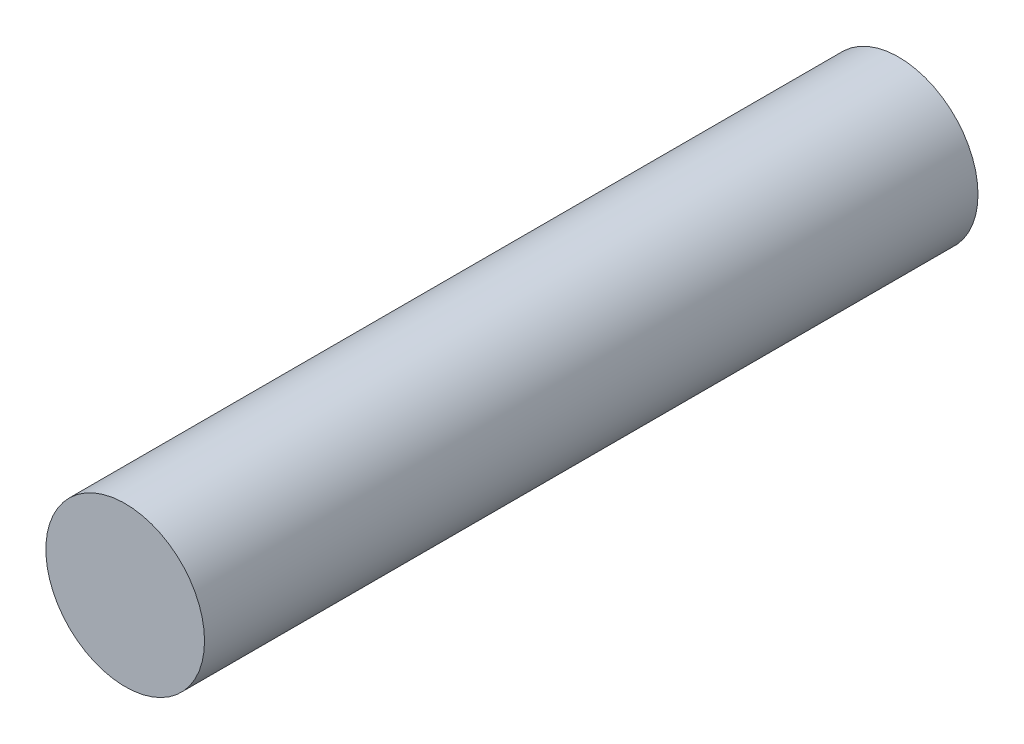
SolidWorks part; units mm, degrees
ref_plane "Front Plane" through (0, 0, 0) normal (0, 0, 1) x (1, 0, 0)
ref_plane "Top Plane" through (0, 0, 0) normal (0, 1, 0) x (1, 0, 0)
ref_plane "Right Plane" through (0, 0, 0) normal (1, 0, 0) x (0, 0, -1)
sketch "Sketch1" plane through (0, 0, 0) normal (0, 0, 1) x (1, 0, 0)
  circle A0 centre (0, 0) radius 7.1807
  dimension "D1" = 14.3614
extrude "Boss-Extrude1" add sketch "Sketch1" along normal mid plane 70
